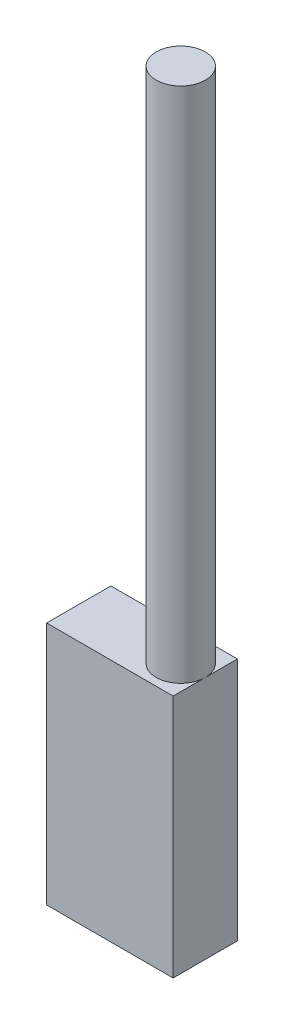
SolidWorks part; units mm, degrees
ref_plane "Front Plane" through (0, 0, 0) normal (0, 0, 1) x (1, 0, 0)
ref_plane "Top Plane" through (0, 0, 0) normal (0, 1, 0) x (1, 0, 0)
ref_plane "Right Plane" through (0, 0, 0) normal (1, 0, 0) x (0, 0, -1)
sketch "Sketch2" plane through (0, 0, 0) normal (0, 0, 1) x (1, 0, 0)
  line L1 (0, 0) -> (25.8, 0)
  line L2 (0, 0) -> (0, 49.8)
  line L3 (0, 49.8) -> (25.8, 49.8)
  line L4 (25.8, 0) -> (25.8, 49.8)
  dimension "D1" = 49.8
  dimension "D2" = 25.8
extrude "Boss-Extrude1" add sketch "Sketch2" along normal blind 13.1
sketch "Sketch3" plane through (0, 49.8, 0) normal (0, 1, 0) x (1, 0, 0)
  line L0 (25.8, -6.55) -> (12.9193, -6.55) construction
  line L1 (25.8, -13.1) -> (25.8, 0) construction
  line L2 (12.9193, -6.55) -> (12.9193, -13.1) construction
  line L3 (25.8, -13.1) -> (0, -13.1) construction
  circle A0 centre (20.8, -6.55) radius 5
  dimension "D1" = 10
extrude "Boss-Extrude2" add sketch "Sketch3" along normal blind 105.5
